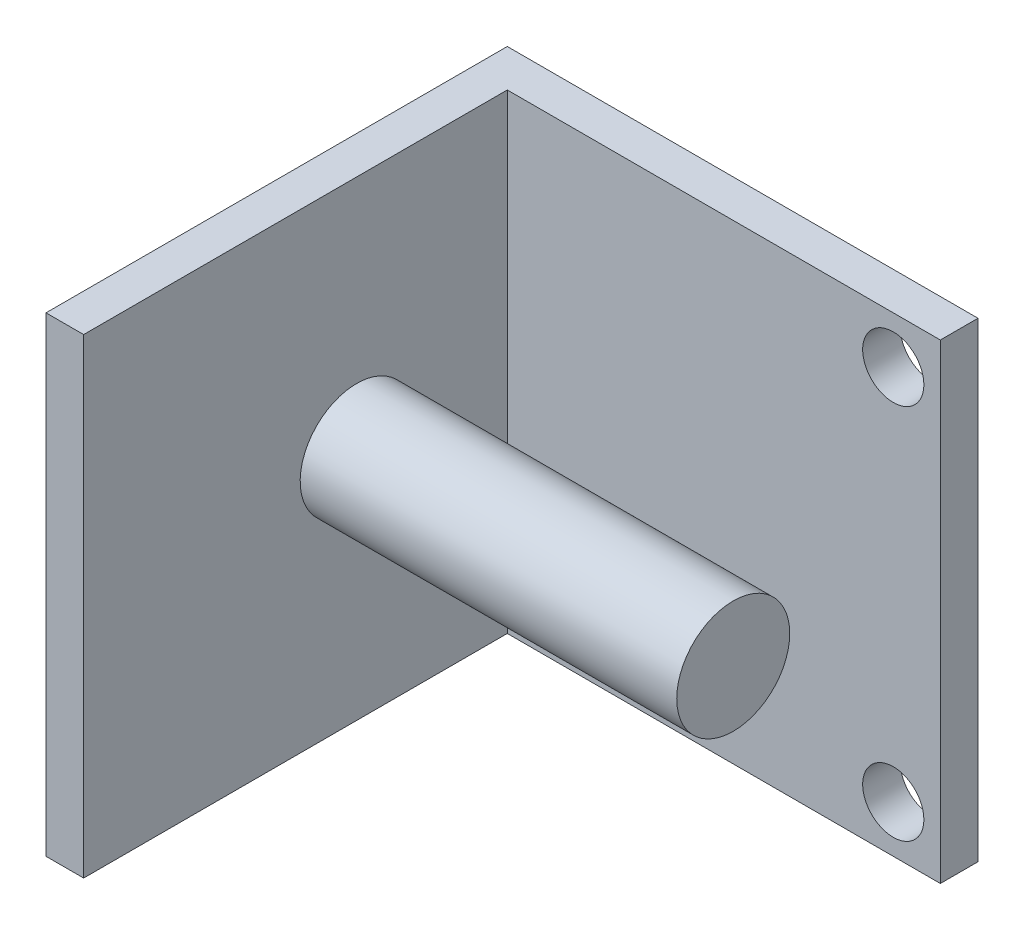
SolidWorks part; units mm, degrees
ref_plane "Front Plane" through (0, 0, 0) normal (0, 0, 1) x (1, 0, 0)
ref_plane "Top Plane" through (0, 0, 0) normal (0, 1, 0) x (1, 0, 0)
ref_plane "Right Plane" through (0, 0, 0) normal (1, 0, 0) x (0, 0, -1)
sketch "Sketch1" plane through (0, 0, 0) normal (0, 0, 1) x (1, 0, 0)
  line L1 (-25, 25) -> (25, 25)
  line L2 (-25, 25) -> (-25, -25)
  line L3 (-25, -25) -> (25, -25)
  line L4 (25, 25) -> (25, -25)
  line L5 (-25, 25) -> (25, -25) construction
  line L6 (-25, -25) -> (25, 25) construction
  point P0 (0, 0)
  dimension "D1" = 50
  dimension "D2" = 50
extrude "Boss-Extrude1" add sketch "Sketch1" along normal blind 4
sketch "Sketch2" plane through (0, 0, 4) normal (0, 0, 1) x (1, 0, 0)
  line L0 (-25, 25) -> (-25, -25) construction
  line L1 (25, 25) -> (-25, 25) construction
  line L2 (-25, -25) -> (25, -25) construction
  line L3 (-25, 25) -> (-25, -25)
  line L4 (-21, 25) -> (-25, 25)
  line L5 (-25, -25) -> (-21, -25)
  line L6 (-21, 25) -> (-21, -25)
  dimension "D1" = 4
extrude "Boss-Extrude2" add sketch "Sketch2" along normal blind 45
sketch "Sketch4" plane through (-21, 0, 0) normal (1, 0, 0) x (0, 0, -1)
  line L0 (0, -25) -> (0, 25) construction
  circle A0 centre (-20, 0) radius 6
  dimension "D1" = 12
  dimension "D2" = 20
extrude "Boss-Extrude3" add sketch "Sketch4" along normal blind 40
sketch "Sketch5" plane through (0, 0, 4) normal (0, 0, 1) x (1, 0, 0)
  line L0 (25, 25) -> (-21, 25) construction
  line L1 (25, -25) -> (25, 25) construction
  line L2 (0, 0) -> (20, 20) construction
  line L3 (0, 0) -> (20, -20) construction
  circle A0 centre (20, 20) radius 3.25
  circle A1 centre (20, -20) radius 3.25
  dimension "D1" = 6.5
  dimension "D2" = 5
  dimension "D3" = 5
  dimension "D5" = 90
  dimension "D4" = 2
extrude "Cut-Extrude1" cut sketch "Sketch5" against normal blind 40
